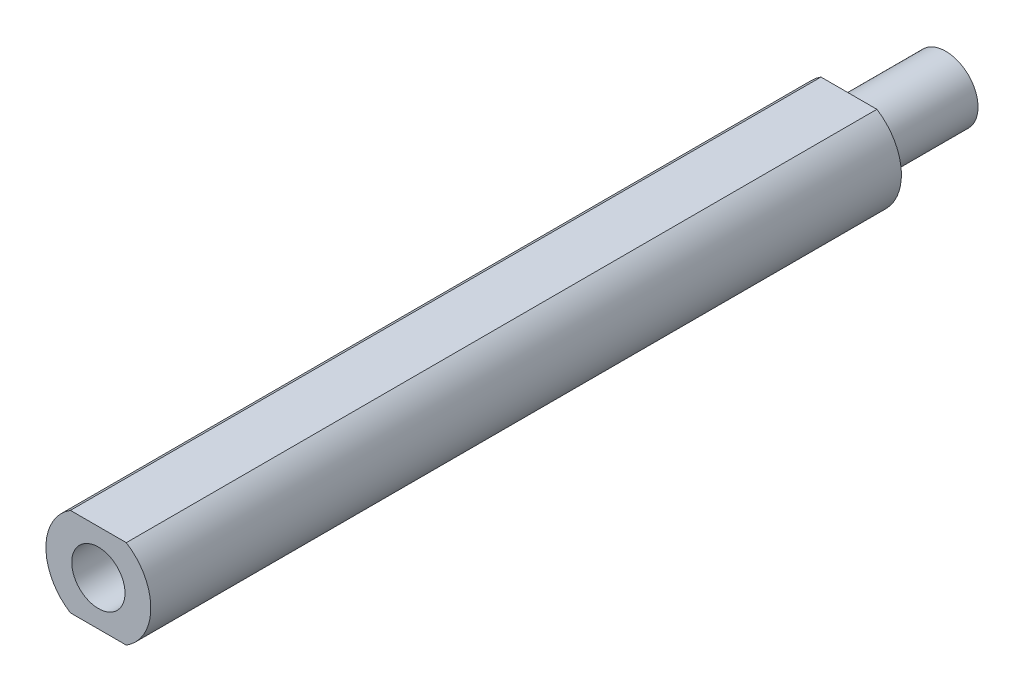
SolidWorks part; units mm, degrees
material "6061 合金"
ref_plane "前视基准面" through (0, 0, 0) normal (0, 0, 1) x (1, 0, 0)
ref_plane "上视基准面" through (0, 0, 0) normal (0, 1, 0) x (1, 0, 0)
ref_plane "右视基准面" through (0, 0, 0) normal (1, 0, 0) x (0, 0, -1)
sketch "草图1" plane through (0, 0, 0) normal (0, 0, 1) x (1, 0, 0)
  line L0 (-1.7321, 2.75) -> (1.7321, 2.75)
  line L7 (-1.7321, -2.75) -> (1.7321, -2.75)
  arc A0 (-1.7321, 2.75) -> (-1.7321, -2.75) centre (0, 0) ccw
  arc A1 (1.7321, -2.75) -> (1.7321, 2.75) centre (0, 0) ccw
  dimension "D1" = 6.5
  dimension "D2" = 5.5
extrude "凸台-拉伸1" add sketch "草图1" along normal blind 46.5
hole_wizard "M4 螺纹孔1" positions "草图2" profile "草图3" tap size "M4" standard "GB"
sketch "草图2" plane through (0, 0, 46.5) normal (0, 0, 1) x (1, 0, 0)
  point P0 (0, 0)
cosmetic thread "孔螺蚊线1"
sketch "草图3" plane through (0, 0, 46.5) normal (1, 0, 0) x (0, -1, 0)
  line L0 (0, 0) -> (0, 12.9914)
  line L1 (0, 12.9914) -> (1.65, 12)
  line L2 (1.65, 12) -> (1.65, 0)
  line L5 (1.65, 0) -> (0, 0)
  line L10 (0, 12.9914) -> (-1.65, 12) construction
  line L11 (0, -6.35) -> (0, 107.95) construction
  dimension "螺纹孔钻头直径" = 3.3
  dimension "螺纹孔钻头深度" = 12
  dimension "导头角度" = 118
sketch "草图4" plane through (0, 0, 0) normal (0, 0, -1) x (-1, 0, 0)
  circle A0 centre (0, 0) radius 2
  dimension "D1" = 4
extrude "凸台-拉伸2" add sketch "草图4" along normal blind 6
cosmetic thread "装饰螺纹线1" parameters "D2"=3.242
